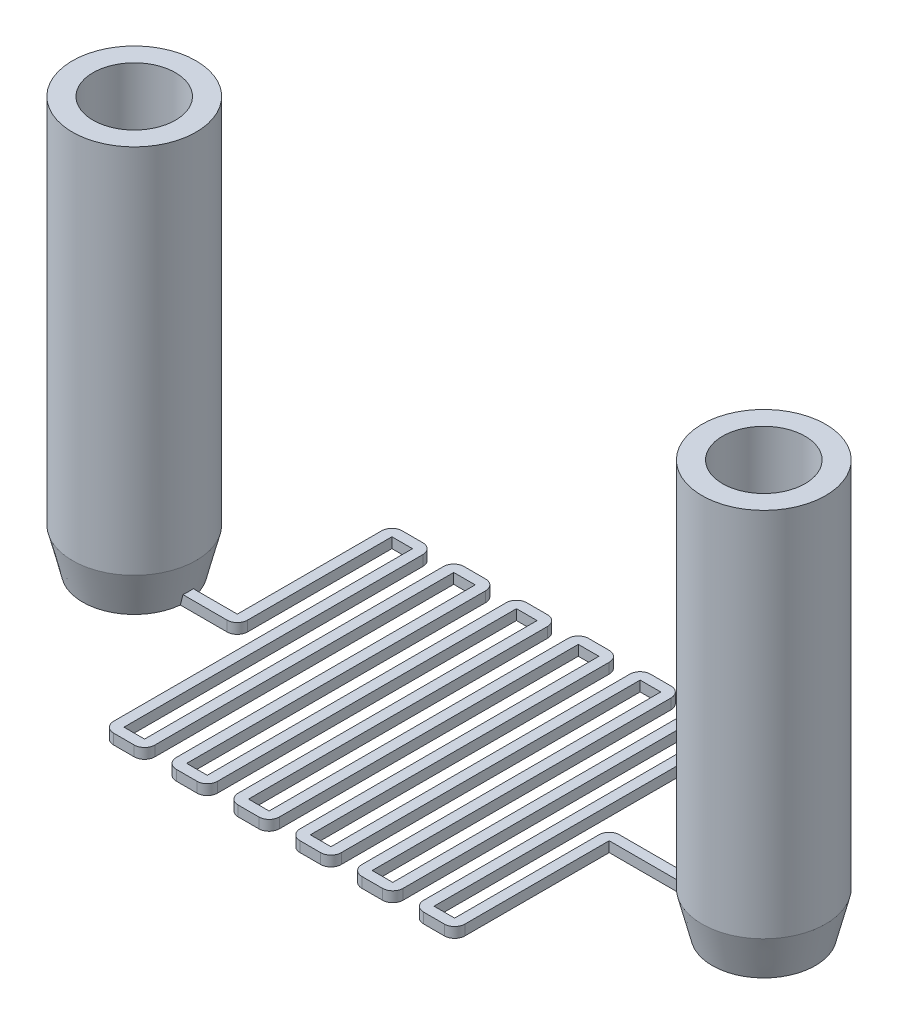
SolidWorks part; units mm, degrees
ref_plane "Front Plane" through (0, 0, 0) normal (0, 0, 1) x (1, 0, 0)
ref_plane "Top Plane" through (0, 0, 0) normal (0, 1, 0) x (1, 0, 0)
ref_plane "Right Plane" through (0, 0, 0) normal (1, 0, 0) x (0, 0, -1)
sketch "Sketch2" plane through (0, 0, 0) normal (0, 1, 0) x (1, 0, 0)
  line L0 (-32.7602, -0.5) -> (-23.2602, -0.5)
  line L2 (1.8255, 15.5) -> (3.8255, 15.5)
  line L3 (13.8255, -0.5) -> (28.3255, -0.5)
  line L30 (-23.2602, 0.5) -> (-23.2602, 14.5)
  line L31 (-19.2602, 14.5) -> (-19.2602, 0)
  line L32 (-19.2602, 0) -> (-19.2602, -14.5)
  line L33 (-17.2602, -14.5) -> (-17.2602, 0)
  line L34 (-17.2602, 0) -> (-17.2602, 14.5)
  line L35 (-13.1745, 14.5) -> (-13.1745, -14.5)
  line L36 (-11.1745, -14.5) -> (-11.1745, 14.5)
  line L37 (-7.1745, 14.5) -> (-7.1745, -14.5)
  line L38 (-5.1745, -14.5) -> (-5.1745, 14.5)
  line L39 (-1.1745, 14.5) -> (-1.1745, -14.5)
  line L40 (0.8255, -14.5) -> (0.8255, 14.5)
  line L41 (4.8255, 14.5) -> (4.8255, -14.5)
  line L42 (6.8255, -14.5) -> (6.8255, 14.5)
  line L43 (10.8255, 14.5) -> (10.8255, -14.5)
  line L44 (-22.2602, 0.5) -> (-22.2602, 14.5)
  line L45 (-20.2602, 14.5) -> (-20.2602, 0)
  line L46 (-20.2602, 0) -> (-20.2602, -14.5)
  line L47 (-16.2602, -14.5) -> (-16.2602, 0)
  line L48 (-16.2602, 0) -> (-16.2602, 14.5)
  line L49 (-14.1745, 14.5) -> (-14.1745, -14.5)
  line L50 (-10.1745, -14.5) -> (-10.1745, 14.5)
  line L51 (-8.1745, 14.5) -> (-8.1745, -14.5)
  line L52 (-4.1745, -14.5) -> (-4.1745, 14.5)
  line L53 (-2.1745, 14.5) -> (-2.1745, -14.5)
  line L54 (1.8255, -14.5) -> (1.8255, 14.5)
  line L55 (3.8255, 14.5) -> (3.8255, -14.5)
  line L56 (7.8255, -14.5) -> (7.8255, 14.5)
  line L57 (9.8255, 14.5) -> (9.8255, -14.5)
  line L58 (-22.2602, 14.5) -> (-20.2602, 14.5)
  line L59 (-16.2602, 14.5) -> (-14.1745, 14.5)
  line L60 (-10.1745, 14.5) -> (-8.1745, 14.5)
  line L61 (-4.1745, 14.5) -> (-2.1745, 14.5)
  line L62 (1.8255, 14.5) -> (3.8255, 14.5)
  line L63 (7.8255, 14.5) -> (9.8255, 14.5)
  line L64 (10.8255, -15.5) -> (12.8255, -15.5)
  line L65 (13.8255, -14.5) -> (13.8255, -0.5)
  line L67 (4.8255, -15.5) -> (6.8255, -15.5)
  line L68 (-1.1745, -15.5) -> (0.8255, -15.5)
  line L69 (-7.1745, -15.5) -> (-5.1745, -15.5)
  line L70 (-13.1745, -15.5) -> (-11.1745, -15.5)
  line L71 (-19.2602, -15.5) -> (-17.2602, -15.5)
  line L72 (-32.7602, 0.5) -> (-23.2602, 0.5)
  line L73 (-22.2602, 15.5) -> (-20.2602, 15.5)
  line L74 (-16.2602, 15.5) -> (-14.1745, 15.5)
  line L75 (-10.1745, 15.5) -> (-8.1745, 15.5)
  line L76 (-4.1745, 15.5) -> (-2.1745, 15.5)
  line L78 (7.8255, 15.5) -> (9.8255, 15.5)
  line L79 (10.8255, -14.5) -> (12.8255, -14.5)
  line L80 (12.8255, -14.5) -> (12.8255, -0.5)
  line L81 (13.8255, 0.5) -> (28.3255, 0.5)
  line L82 (4.8255, -14.5) -> (6.8255, -14.5)
  line L83 (-1.1745, -14.5) -> (0.8255, -14.5)
  line L84 (-7.1745, -14.5) -> (-5.1745, -14.5)
  line L85 (-13.1745, -14.5) -> (-11.1745, -14.5)
  line L86 (-19.2602, -14.5) -> (-17.2602, -14.5)
  arc A26 (-23.2602, -0.5) -> (-22.2602, 0.5) centre (-23.2602, 0.5) ccw
  arc A39 (9.8255, -14.5) -> (10.8255, -15.5) centre (10.8255, -14.5) ccw
  arc A40 (12.8255, -15.5) -> (13.8255, -14.5) centre (12.8255, -14.5) ccw
  arc A42 (3.8255, -14.5) -> (4.8255, -15.5) centre (4.8255, -14.5) ccw
  arc A43 (6.8255, -15.5) -> (7.8255, -14.5) centre (6.8255, -14.5) ccw
  arc A44 (-2.1745, -14.5) -> (-1.1745, -15.5) centre (-1.1745, -14.5) ccw
  arc A45 (0.8255, -15.5) -> (1.8255, -14.5) centre (0.8255, -14.5) ccw
  arc A46 (-8.1745, -14.5) -> (-7.1745, -15.5) centre (-7.1745, -14.5) ccw
  arc A47 (-5.1745, -15.5) -> (-4.1745, -14.5) centre (-5.1745, -14.5) ccw
  arc A48 (-14.1745, -14.5) -> (-13.1745, -15.5) centre (-13.1745, -14.5) ccw
  arc A49 (-11.1745, -15.5) -> (-10.1745, -14.5) centre (-11.1745, -14.5) ccw
  arc A50 (-20.2602, -14.5) -> (-19.2602, -15.5) centre (-19.2602, -14.5) ccw
  arc A51 (-17.2602, -15.5) -> (-16.2602, -14.5) centre (-17.2602, -14.5) ccw
  arc A53 (-23.2602, 14.5) -> (-22.2602, 15.5) centre (-22.2602, 14.5) cw
  arc A54 (-19.2602, 14.5) -> (-20.2602, 15.5) centre (-20.2602, 14.5) ccw
  arc A55 (-17.2602, 14.5) -> (-16.2602, 15.5) centre (-16.2602, 14.5) cw
  arc A56 (-14.1745, 15.5) -> (-13.1745, 14.5) centre (-14.1745, 14.5) cw
  arc A57 (-11.1745, 14.5) -> (-10.1745, 15.5) centre (-10.1745, 14.5) cw
  arc A58 (-8.1745, 15.5) -> (-7.1745, 14.5) centre (-8.1745, 14.5) cw
  arc A59 (-5.1745, 14.5) -> (-4.1745, 15.5) centre (-4.1745, 14.5) cw
  arc A60 (-2.1745, 15.5) -> (-1.1745, 14.5) centre (-2.1745, 14.5) cw
  arc A61 (0.8255, 14.5) -> (1.8255, 15.5) centre (1.8255, 14.5) cw
  arc A62 (3.8255, 15.5) -> (4.8255, 14.5) centre (3.8255, 14.5) cw
  arc A63 (6.8255, 14.5) -> (7.8255, 15.5) centre (7.8255, 14.5) cw
  arc A64 (9.8255, 15.5) -> (10.8255, 14.5) centre (9.8255, 14.5) cw
  arc A67 (12.8255, -0.5) -> (13.8255, 0.5) centre (13.8255, -0.5) cw
  arc A78 (-32.7602, 0.5) -> (-32.7602, -0.5) centre (-32.7602, 0) ccw
  arc A79 (28.3255, -0.5) -> (28.3255, 0.5) centre (28.3255, 0) ccw
  point P4 (0, 0)
  point P35 (-22.7602, 0)
  point P38 (-19.7602, -15)
  point P41 (-16.7602, -15)
  point P44 (-13.6745, -15)
  point P47 (-10.6745, -15)
  point P50 (-7.6745, -15)
  point P53 (-4.6745, -15)
  point P56 (-1.6745, -15)
  point P59 (1.3255, -15)
  point P62 (4.3255, -15)
  point P65 (7.3255, -15)
  point P68 (13.3255, 0)
  point P71 (10.3255, -15)
  point P74 (13.3255, -15)
  point P77 (10.3255, 15)
  point P80 (7.3255, 15)
  point P83 (4.3255, 15)
  point P86 (1.3255, 15)
  point P89 (-1.6745, 15)
  point P92 (-4.6745, 15)
  point P95 (-7.6745, 15)
  point P100 (-10.6745, 15)
  point P105 (-19.7602, 15)
  point P108 (-22.7602, 15)
  dimension "D3" = 3
  dimension "D5" = 3
  dimension "D6" = 3
  dimension "D7" = 3
  dimension "D8" = 3
  dimension "D9" = 3
  dimension "D10" = 3
  dimension "D11" = 3
  dimension "D12" = 3
  dimension "D13" = 3
  dimension "D14" = 3
extrude "Boss-Extrude1" add sketch "Sketch2" along normal blind 1
ref_plane "Plane1" through (0, 0, 0) normal (0, 0, 1) x (1, 0, 0)
sketch "Sketch3" plane through (0, 0, 0) normal (0, 0, 1) x (1, 0, 0)
  line L0 (-32.7602, 0) -> (-37.7602, 0)
  line L2 (-32.7602, 0) -> (-32.7602, 40)
  line L3 (-32.7602, 40) -> (-38.7602, 40)
  line L4 (-38.7602, 40) -> (-38.7602, 4)
  line L5 (-38.7602, 4) -> (-37.7602, 0)
  dimension "D1" = 5
  dimension "D3" = 40
  dimension "D4" = 6
revolve "Revolve1" add sketch "Sketch3" angle 360 about L2
ref_plane "Plane2" through (0, 0, 0) normal (0, 0, 1) x (1, 0, 0)
sketch "Sketch4" plane through (0, 0, 0) normal (0, 0, 1) x (1, 0, 0)
  line L0 (28.3255, 0) -> (33.3255, 0)
  line L2 (28.3255, 0) -> (28.3255, 40)
  line L3 (28.3255, 40) -> (34.3255, 40)
  line L4 (34.3255, 40) -> (34.3255, 4)
  line L5 (34.3255, 4) -> (33.3255, 0)
  dimension "D1" = 5
  dimension "D3" = 40
  dimension "D4" = 6
revolve "Revolve2" add sketch "Sketch4" angle 360 about L2
sketch "Sketch5" plane through (0, 40, 0) normal (0, 1, 0) x (1, 0, 0)
  circle A0 centre (-32.7602, 0) radius 4
  circle A1 centre (28.3255, 0) radius 4
  dimension "D1" = 8
  dimension "D2" = 8
extrude "Cut-Extrude1" cut sketch "Sketch5" against normal blind 35
